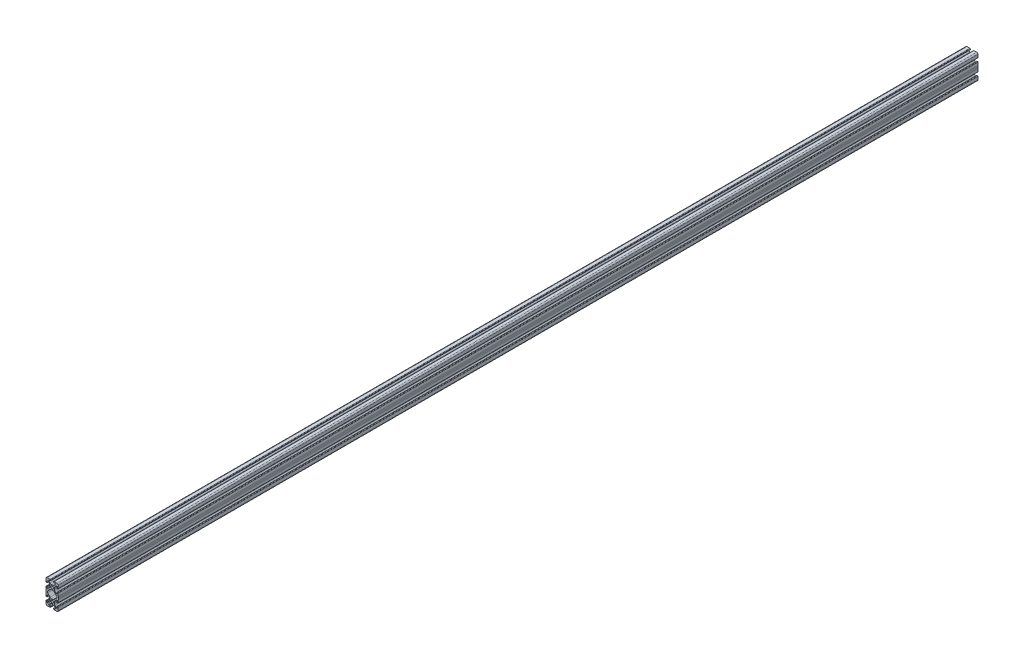
SolidWorks part; units mm, degrees
ref_plane "Front Plane" through (0, 0, 0) normal (0, 0, 1) x (1, 0, 0)
ref_plane "Top Plane" through (0, 0, 0) normal (0, 1, 0) x (1, 0, 0)
ref_plane "Right Plane" through (0, 0, 0) normal (1, 0, 0) x (0, 0, -1)
sketch "Sketch1" plane through (0, 0, 0) normal (0, 0, 1) x (1, 0, 0)
  line L0 (0, 10) -> (0, 20) construction
  line L1 (0, 10) -> (10, 10) construction
  line L2 (0, 10) -> (-10, 20) construction
  line L3 (-7.9302, 19.9988) -> (-3.2721, 19.8361)
  line L4 (-10, 20) -> (0, 20) construction
  line L6 (-2.8352, 18.0198) -> (-4.953, 18.0937)
  line L10 (0, 13.6) -> (-1.1022, 13.6)
  line L11 (-3.2236, 14.4787) -> (-5.5244, 16.7796)
  line L24 (0, 10) -> (-10, 10) construction
  line L25 (-10, 10) -> (0, 10) construction
  line L27 (-10, 0) -> (-10, 20) construction
  line L28 (0, 20) -> (10, 20) construction
  line L29 (-2.5249, 18.3091) -> (-2.5005, 19.0087)
  line L30 (-10, -20) -> (10, -20) construction
  line L31 (0, 20) -> (0, -20) construction
  arc A0 (-9.4142, 19.4142) -> (-7.9302, 19.9988) centre (-8, 18) cw
  arc A5 (-3.2721, 19.8361) -> (-2.5005, 19.0087) centre (-3.3, 19.0366) cw
  arc A6 (-1.1022, 13.6) -> (-3.2236, 14.4787) centre (-1.1022, 16.6) cw
  circle A16 centre (0, 10) radius 2.15
  arc A18 (-5.5244, 16.7796) -> (-4.953, 18.0937) centre (-4.9799, 17.3241) cw
  arc A20 (-2.8352, 18.0198) -> (-2.5249, 18.3091) centre (-2.8247, 18.3196) ccw
  point P15 (0, -20)
  point P24 (0, 0)
  point P42 (-2.3449, 13.6)
  point P80 (-10, 10)
  dimension "D11" = 2
  dimension "D15" = 3
  dimension "Center Hole Diameter" = 4.3
  dimension "D7" = 0.8
  dimension "D8" = 0.3
  dimension "D4" = 0.7701
  dimension "D1" = 45
  dimension "D2" = 2
  dimension "Rail Width" = 20
  dimension "T-Slot Depth" = 6.4
  dimension "D9" = 1.8
  dimension "D23" = 7.2
  dimension "D5" = 11.5
  dimension "T-Slot Width" = 5
  dimension "D3" = 1.775
  dimension "D6" = 9.9598
  dimension "Rail Height" = 40
sketch "Sketch2" plane through (0, 0, 0) normal (1, 0, 0) x (0, 0, -1)
  line L0 (-1524, 0) -> (1524, 0)
  line L1 (-1524, -20) -> (-1524, 20)
  line L2 (0, 10) -> (0, 20) construction
  line L3 (0, 0) -> (0, 20) construction
  line L4 (1524, -20) -> (1524, 20)
  line L5 (-10, 10) -> (10, 10) construction
  point P0 (-1491.5, 0)
  point P3 (0, 0)
  point P7 (1491.5, 0)
  point P11 (-1524, 0)
  point P14 (1524, 0)
  point P23 (0, 10)
  dimension "D1" = 32.5
  dimension "Length" = 3048
sketch "Sketch3" plane through (0, 0, 0) normal (0, 0, 1) x (1, 0, 0)
  line L0 (-2.5249, 18.3091) -> (-2.5005, 19.0087) construction
  line L1 (0, 10) -> (-10, 20) construction
  line L2 (0, 10) -> (-10, 20) construction
  line L5 (-7.9302, 19.9988) -> (-3.2721, 19.8361) construction
  line L6 (-2.8352, 18.0198) -> (-4.953, 18.0937) construction
  line L7 (-8.3091, 7.4751) -> (-9.0087, 7.4995)
  line L17 (-2.5249, 18.3091) -> (-2.5005, 19.0087)
  line L19 (-2.8352, 18.0198) -> (-4.953, 18.0937)
  line L21 (-3.6, 10) -> (0, 10) construction
  line L22 (-3.6, 8.8978) -> (-3.6, 11.1022)
  line L23 (-4.4787, 13.2236) -> (-6.7796, 15.5244)
  line L42 (-3.2236, 14.4787) -> (-5.5244, 16.7796) construction
  line L43 (0, 13.6) -> (-1.1022, 13.6) construction
  line L44 (-7.9302, 19.9988) -> (-3.2721, 19.8361)
  line L47 (-3.2236, 14.4787) -> (-5.5244, 16.7796)
  line L48 (1.1022, 13.6) -> (-1.1022, 13.6)
  line L59 (0, 13.6) -> (0, 12.15) construction
  line L60 (-9.9988, 17.9302) -> (-9.8361, 13.2721)
  line L61 (-8.0198, 12.8352) -> (-8.0937, 14.953)
  line L62 (-8.3091, 12.5249) -> (-9.0087, 12.5005)
  line L63 (-8.0198, 7.1648) -> (-8.0937, 5.047)
  line L64 (-9.9868, 2.4128) -> (-9.8361, 6.7279)
  line L65 (1.1022, 6.4) -> (-1.1022, 6.4)
  line L66 (-3.2236, 5.5213) -> (-7.3307, 1.4142)
  line L68 (-4.4787, 6.7764) -> (-6.7796, 4.4756)
  line L73 (10, 0) -> (-10, 0) construction
  line L75 (-10, 0) -> (-9.999, 1.7266)
  line L77 (10, 0) -> (9.999, 1.7266)
  line L78 (4.4787, 6.7764) -> (6.7796, 4.4756)
  line L79 (3.2236, 5.5213) -> (7.3307, 1.4142)
  line L81 (9.9868, 2.4128) -> (9.8361, 6.7279)
  line L82 (8.0198, 7.1648) -> (8.0937, 5.047)
  line L83 (8.3091, 12.5249) -> (9.0087, 12.5005)
  line L84 (8.0198, 12.8352) -> (8.0937, 14.953)
  line L85 (9.9988, 17.9302) -> (9.8361, 13.2721)
  line L87 (3.2236, 14.4787) -> (5.5244, 16.7796)
  line L88 (7.9302, 19.9988) -> (3.2721, 19.8361)
  line L89 (4.4787, 13.2236) -> (6.7796, 15.5244)
  line L90 (3.6, 8.8978) -> (3.6, 11.1022)
  line L91 (2.8352, 18.0198) -> (4.953, 18.0937)
  line L92 (2.5249, 18.3091) -> (2.5005, 19.0087)
  line L93 (8.3091, 7.4751) -> (9.0087, 7.4995)
  line L94 (-10, 0) -> (-7.9165, 0)
  line L96 (7.9165, 0) -> (10, 0)
  arc A0 (-7.9302, 19.9988) -> (-9.4142, 19.4142) centre (-8, 18) ccw construction
  arc A1 (-2.8352, 18.0198) -> (-2.5249, 18.3091) centre (-2.8247, 18.3196) ccw construction
  arc A3 (-2.8352, 18.0198) -> (-2.5249, 18.3091) centre (-2.8247, 18.3196) ccw
  arc A5 (-7.9302, 19.9988) -> (-9.9988, 17.9302) centre (-8, 18) ccw
  arc A10 (-3.2236, 5.5213) -> (-1.1022, 6.4) centre (-1.1022, 3.4) cw
  circle A13 centre (0, 10) radius 2.15 construction
  circle A14 centre (0, 10) radius 2.15
  arc A15 (-4.4787, 13.2236) -> (-3.6, 11.1022) centre (-6.6, 11.1022) cw
  arc A16 (-8.0937, 14.953) -> (-6.7796, 15.5244) centre (-7.3241, 14.9799) cw
  arc A17 (-9.0087, 12.5005) -> (-9.8361, 13.2721) centre (-9.0366, 13.3) cw
  arc A18 (-8.0198, 12.8352) -> (-8.3091, 12.5249) centre (-8.3196, 12.8247) cw
  arc A36 (-2.5005, 19.0087) -> (-3.2721, 19.8361) centre (-3.3, 19.0366) ccw construction
  arc A38 (-4.953, 18.0937) -> (-5.5244, 16.7796) centre (-4.9799, 17.3241) ccw construction
  arc A39 (-3.2236, 14.4787) -> (-1.1022, 13.6) centre (-1.1022, 16.6) ccw construction
  arc A41 (-2.5005, 19.0087) -> (-3.2721, 19.8361) centre (-3.3, 19.0366) ccw
  arc A43 (-4.953, 18.0937) -> (-5.5244, 16.7796) centre (-4.9799, 17.3241) ccw
  arc A44 (-3.2236, 14.4787) -> (-1.1022, 13.6) centre (-1.1022, 16.6) ccw
  arc A47 (-8.0198, 7.1648) -> (-8.3091, 7.4751) centre (-8.3196, 7.1753) ccw
  arc A48 (-9.0087, 7.4995) -> (-9.8361, 6.7279) centre (-9.0366, 6.7) ccw
  arc A49 (-8.0937, 5.047) -> (-6.7796, 4.4756) centre (-7.3241, 5.0201) ccw
  arc A50 (-4.4787, 6.7764) -> (-3.6, 8.8978) centre (-6.6, 8.8978) ccw
  arc A54 (-7.9165, 0) -> (-7.3307, 1.4142) centre (-5.9165, 0) cw
  arc A55 (-9.999, 1.7266) -> (-9.9868, 2.4128) centre (10.001, 1.7148) cw
  arc A56 (9.999, 1.7266) -> (9.9868, 2.4128) centre (-10.001, 1.7148) ccw
  arc A57 (7.9165, 0) -> (7.3307, 1.4142) centre (5.9165, 0) ccw
  arc A58 (4.4787, 6.7764) -> (3.6, 8.8978) centre (6.6, 8.8978) cw
  arc A59 (8.0937, 5.047) -> (6.7796, 4.4756) centre (7.3241, 5.0201) cw
  arc A60 (9.0087, 7.4995) -> (9.8361, 6.7279) centre (9.0366, 6.7) cw
  arc A61 (8.0198, 7.1648) -> (8.3091, 7.4751) centre (8.3196, 7.1753) cw
  arc A62 (3.2236, 14.4787) -> (1.1022, 13.6) centre (1.1022, 16.6) cw
  arc A63 (4.953, 18.0937) -> (5.5244, 16.7796) centre (4.9799, 17.3241) cw
  arc A64 (2.5005, 19.0087) -> (3.2721, 19.8361) centre (3.3, 19.0366) cw
  arc A65 (8.0198, 12.8352) -> (8.3091, 12.5249) centre (8.3196, 12.8247) ccw
  arc A66 (9.0087, 12.5005) -> (9.8361, 13.2721) centre (9.0366, 13.3) ccw
  arc A67 (8.0937, 14.953) -> (6.7796, 15.5244) centre (7.3241, 14.9799) ccw
  arc A68 (4.4787, 13.2236) -> (3.6, 11.1022) centre (6.6, 11.1022) ccw
  arc A70 (3.2236, 5.5213) -> (1.1022, 6.4) centre (1.1022, 3.4) ccw
  arc A71 (7.9302, 19.9988) -> (9.9988, 17.9302) centre (8, 18) cw
  arc A72 (2.8352, 18.0198) -> (2.5249, 18.3091) centre (2.8247, 18.3196) cw
  point P59 (-9.9988, 2.0698)
  point P71 (0, 0)
  point P116 (0, 6.4)
  dimension "D1" = 20
extrude "Boss-Extrude1" add sketch "Sketch3" along normal mid plane 3048
pattern_circular "CirPattern1" count 2 over 360 about axis through (0, 0, 0) along (0, 0, 1) of "Boss-Extrude1"
ref_plane "Contact Plane 1" through (0, 20, 0) normal (0, 1, 0) x (1, 0, 0)
ref_plane "Contact Plane 2" through (10, 10, 0) normal (1, 0, 0) x (0, 0, -1)
ref_plane "Contact Plane 3" through (0, -20, 0) normal (0, -1, 0) x (-1, 0, 0)
ref_plane "Contact Plane 4" through (-10, 10, 0) normal (-1, 0, 0) x (0, 0, 1)
sketch "Sketch4" plane through (3.6, 0, 0) normal (1, 0, 0) x (0, 0, -1)
  line L0 (-1524, -20) -> (1524, -20) construction
  line L1 (-1524, 20) -> (-24, 20)
  line L2 (-1524, 20) -> (-1524, -20)
  line L3 (-1524, -20) -> (-24, -20)
  line L4 (-24, 20) -> (-24, -20)
extrude "Cut-Extrude1" cut sketch "Sketch4" against normal blind 23 and the other way blind 14 flip side to cut
equation "\"D1@Sketch2\"=\"Rail Width@Sketch1\"*1.625"
equation "\"D1@Boss-Extrude1\" = \"Length@Sketch2\""
equation "\"D1@Sketch3\"=\"Rail Width@Sketch1\""
